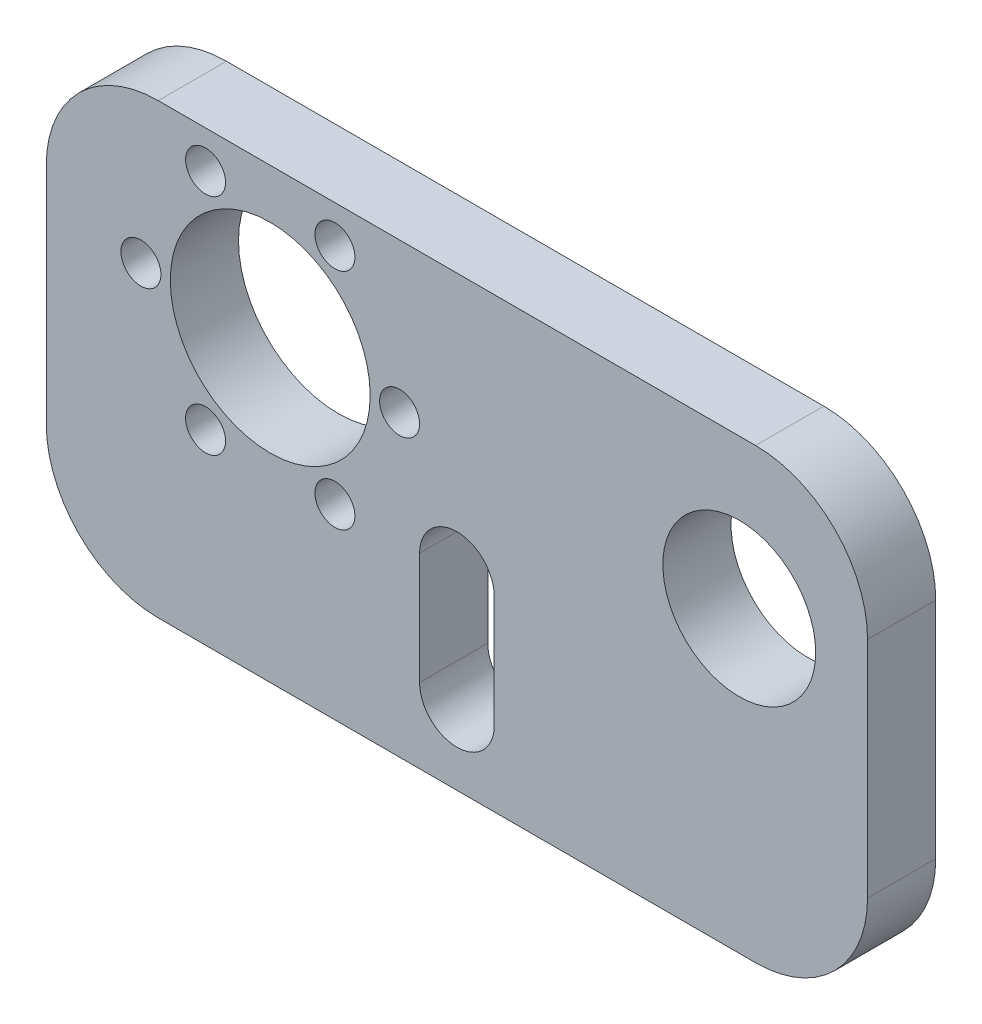
SolidWorks part; units mm, degrees
material "Balsa"
ref_plane "Front Plane" through (0, 0, 0) normal (0, 0, 1) x (1, 0, 0)
ref_plane "Top Plane" through (0, 0, 0) normal (0, 1, 0) x (1, 0, 0)
ref_plane "Right Plane" through (0, 0, 0) normal (1, 0, 0) x (0, 0, -1)
sketch "Sketch1" plane through (0, 0, 0) normal (0, 0, 1) x (1, 0, 0)
  line L0 (0, 38.1) -> (69.85, 38.1)
  line L1 (69.85, 38.1) -> (69.85, 0)
  line L2 (0, 0) -> (0, 38.1)
  line L3 (69.85, 0) -> (0, 0)
  line L14 (58.9398, 0) -> (58.9398, 25.4) construction
  line L18 (19.05, 25.4) -> (0, 25.4) construction
  line L25 (58.9398, 25.4) -> (19.05, 25.4) construction
  circle A9 centre (58.9398, 25.4) radius 6.5
  circle A14 centre (19.05, 25.4) radius 8.5
  dimension "D3" = 39.8898
  dimension "D16" = 13
  dimension "D24" = 17
  dimension "D1" = 38.1
  dimension "D5" = 25.4
  dimension "D6" = 25.4
  dimension "D7" = 69.85
  dimension "D4" = 19.05
extrude "Boss-Extrude1" add sketch "Sketch1" along normal blind 5.8
sketch "Sketch3" plane through (0, 0, 5.8) normal (0, 0, 1) x (1, 0, 0)
  line L0 (17.3293, 29.881) -> (52.0927, 43.2305) construction
  line L1 (17.3293, 20.919) -> (52.0927, 7.5695) construction
  line L20 (19.05, 25.4) -> (58.9398, 25.4) construction
  line L21 (34.925, 25.4) -> (34.925, 6.35) construction
  line L22 (31.75, 15.875) -> (31.75, 6.35)
  line L23 (38.1, 15.875) -> (38.1, 6.35)
  arc A0 (17.3293, 29.881) -> (17.3293, 20.919) centre (19.05, 25.4) ccw construction
  arc A1 (52.0927, 7.5695) -> (52.0927, 43.2305) centre (58.9398, 25.4) ccw construction
  circle A8 centre (58.9398, 25.4) radius 19.1 construction
  arc A21 (38.1, 15.875) -> (31.75, 15.875) centre (34.925, 15.875) ccw
  arc A22 (31.75, 6.35) -> (38.1, 6.35) centre (34.925, 6.35) ccw
  circle A23 centre (34.925, 15.875) radius 8.7312 construction
  dimension "D1" = 4.8
  dimension "D2" = 19.1
  dimension "D3" = 6.35
  dimension "D9" = 9.525
  dimension "D4" = 9.525
  dimension "D10" = 15.875
hole_wizard "M3 Clearance Hole1" positions "Sketch7" profile "Sketch6" hole size "M3" standard "Ansi Metric" end condition through all
sketch "Sketch7" plane through (0, 0, 5.8) normal (0, 0, 1) x (1, 0, 0)
  line L32 (19.05, 25.4) -> (30.05, 25.4) construction
  line L34 (19.05, 25.4) -> (24.55, 15.8737) construction
  line L35 (19.05, 25.4) -> (13.55, 15.8737) construction
  line L36 (19.05, 25.4) -> (8.05, 25.4) construction
  line L37 (19.05, 25.4) -> (13.55, 34.9263) construction
  line L38 (19.05, 25.4) -> (24.55, 34.9263) construction
  circle A2 centre (19.05, 25.4) radius 11 construction
  point P112 (30.05, 25.4)
  point P144 (24.55, 34.9263)
  point P146 (13.55, 34.9263)
  point P148 (8.05, 25.4)
  point P150 (13.55, 15.8737)
  point P152 (24.55, 15.8737)
  dimension "D1" = 11
  dimension "D2" = 6
sketch "Sketch6" plane through (30.05, 25.4, 5.8) normal (1, 0, 0) x (0, -1, 0)
  line L0 (0, 0) -> (0, 5.8)
  line L1 (0, 5.8) -> (1.7, 5.8)
  line L2 (1.7, 5.8) -> (1.7, 0)
  line L5 (1.7, 0) -> (0, 0)
  line L11 (0, -6.35) -> (0, 107.95) construction
  dimension "Thru Hole Dia." = 3.4
  dimension "Thru Hole Depth" = 5.8
extrude "Cut-Extrude1" cut sketch "Sketch3" against normal through all
fillet "Fillet1" radius 9.525 4 edges at (0, 0, 2.9) (69.85, 0, 2.9) (69.85, 38.1, 2.9) (0, 38.1, 2.9)
